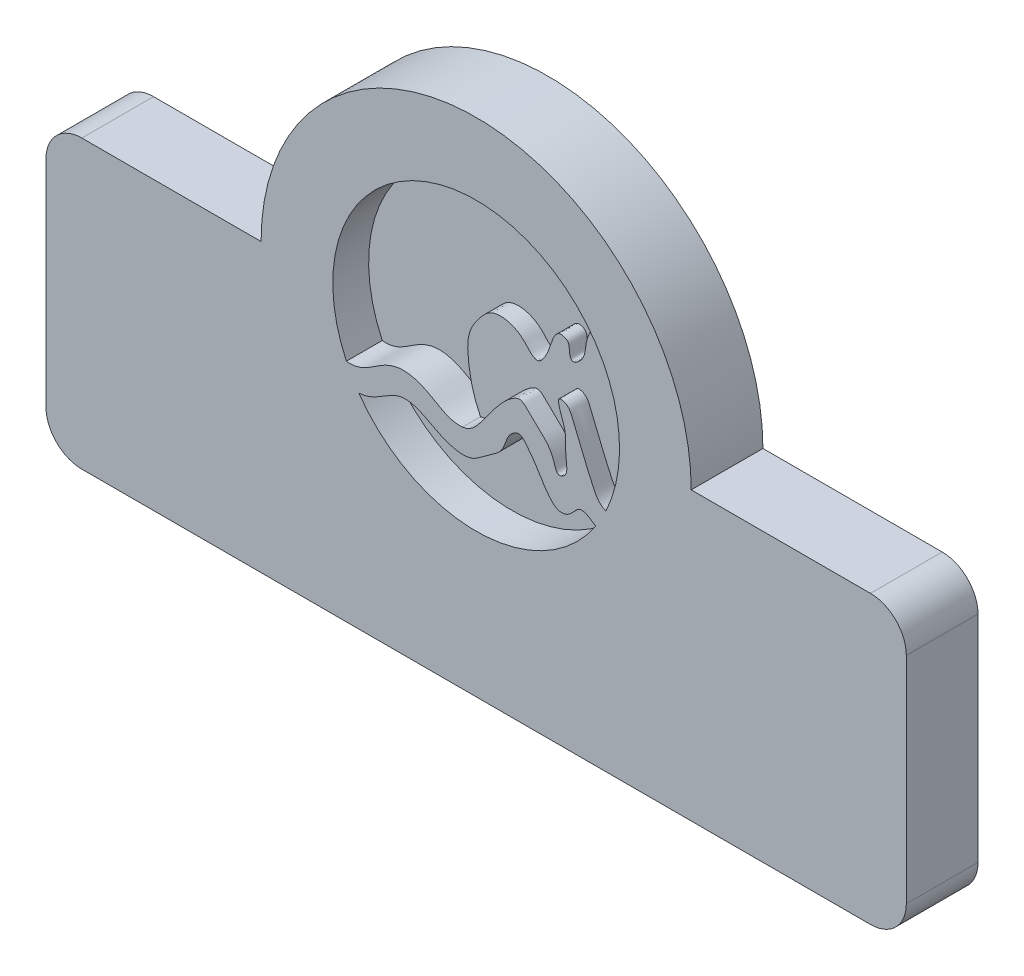
SolidWorks part; units mm, degrees
other "Camera1"
other "Camera2"
other "Camera3"
ref_plane "Front Plane" through (0, 0, 0) normal (0, 0, 1) x (1, 0, 0)
ref_plane "Top Plane" through (0, 0, 0) normal (0, 1, 0) x (1, 0, 0)
ref_plane "Right Plane" through (0, 0, 0) normal (1, 0, 0) x (0, 0, -1)
sketch "Sketch1" plane through (0, 0, 0) normal (0, 0, 1) x (1, 0, 0)
  line L0 (6.9108, 13.8216) -> (34.554, 13.8216) construction
  line L1 (6.9108, 13.8216) -> (34.554, 13.8216) construction
  line L2 (35.7853, 16.1395) -> (54.8353, 16.1395)
  line L3 (-21.3647, -9.2605) -> (54.8353, -9.2605)
  line L4 (-21.3647, -9.2605) -> (-21.3647, 16.1395)
  line L5 (-21.3647, 16.1395) -> (-2.3147, 16.1395)
  line L6 (54.8353, -9.2605) -> (54.8353, 16.1395)
  arc A0 (35.7853, 16.1395) -> (-2.3147, 16.1395) centre (16.7353, 16.1395) ccw
  point P10 (16.7353, -9.2605)
  dimension "D1" = 19.05
  dimension "D2" = 25.4
  dimension "D3" = 76.2
extrude "Boss-Extrude3" add sketch "Sketch1" along normal blind 6.35
sketch "Sketch2" plane through (0, 0, 0) normal (0, 0, 1) x (1, 0, 0)
  line L0 (6.9108, 13.8216) -> (34.554, 13.8216) construction
  line L1 (6.9108, 13.8216) -> (34.554, 13.8216) construction
  line L3 (-21.3647, -9.2605) -> (54.8353, -9.2605)
  line L4 (-21.3647, -9.2605) -> (-21.3647, 16.1395)
  line L5 (-21.3647, 16.1395) -> (4.0353, 16.1395)
  line L6 (54.8353, -9.2605) -> (54.8353, 16.1395)
  line L7 (29.4353, 16.1395) -> (54.8353, 16.1395)
  circle A0 centre (16.7353, 16.1395) radius 12.7
  spline S0 degree 3 poles (5.2422, 10.736) (6.7181, 10.5583) (7.9181, 12.0335) (10.4689, 12.7659) (12.4429, 12.0981) (14.04, 10.9311) (16.2264, 10.6186) (17.4992, 12.5179) (18.6877, 14.1015) (19.6579, 15.1072) (20.7366, 15.6711) (21.5924, 14.6574) (22.7186, 13.7475) (23.5698, 12.7033) (23.8626, 11.2746) (24.9534, 11.6978) (24.5407, 13.3498) (24.8083, 15.1398) (24.095, 16.3012) (23.9989, 17.3316) (24.934, 17.3133) (25.3682, 16.0395) (25.9915, 14.7265) (26.4068, 13.4846) (27.1285, 12.1461) (27.37, 11.104) (28.2285, 10.736) knots 0 0 0 0 0.103449 0.139242 0.205578 0.258602 0.299466 0.363653 0.418235 0.461509 0.476758 0.506043 0.548409 0.597042 0.622241 0.632003 0.675048 0.726967 0.779124 0.786559 0.795901 0.835777 0.878716 0.917237 0.938498 1 1 1 1
  spline S1 degree 3 poles (6.3413, 8.8418) (7.3529, 8.8928) (8.4397, 9.7204) (10.0783, 10.5483) (11.6016, 10.3368) (13.0104, 9.4793) (14.603, 8.7601) (16.3539, 8.6272) (17.6381, 9.777) (19.2522, 10.6455) (19.4083, 12.2512) (20.6019, 13.0206) (21.5067, 11.9378) (22.2898, 10.7945) (23.033, 9.4552) (23.9852, 8.5414) (25.1785, 8.7836) (25.8581, 10.2364) (27.0204, 9.3268) (27.3242, 9.1277) knots 0 0 0 0 0.111112 0.158804 0.207675 0.281443 0.349359 0.412439 0.469148 0.544608 0.609897 0.643349 0.67797 0.748785 0.815451 0.856727 0.888905 0.942631 1 1 1 1
  spline S2 degree 3 poles (15.5303, 10.8283) (14.8939, 12.0951) (14.4389, 13.9813) (14.3435, 16.7343) (15.2691, 18.2447) (16.5062, 19.5074) (18.14, 19.4662) (19.332, 18.7362) (19.9024, 17.9655) (20.6817, 17.4716) (21.4483, 18.509) (21.7334, 19.5035) (22.2913, 20.9391) (23.5141, 20.4969) (23.333, 19.7355) (23.6787, 18.9513) (24.8928, 19.8566) (24.7041, 21.7986) (25.937, 23.3158) (26.6866, 24.0301) knots 0 0 0 0 0.163827 0.228295 0.314759 0.363733 0.427294 0.487534 0.520272 0.543413 0.580046 0.637018 0.68948 0.715614 0.7546 0.768001 0.802503 0.870836 1 1 1 1
  dimension "D1" = 25.4
  dimension "D2" = 25.4
  dimension "D3" = 76.2
sketch "Sketch4" plane through (0, 0, 0) normal (0, 0, 1) x (1, 0, 0)
  line L0 (6.9108, 13.8216) -> (34.554, 13.8216) construction
  line L1 (6.9108, 13.8216) -> (34.554, 13.8216) construction
  line L3 (-21.3647, -9.2605) -> (54.8353, -9.2605)
  line L4 (-21.3647, -9.2605) -> (-21.3647, 16.1395)
  line L5 (-21.3647, 16.1395) -> (4.0353, 16.1395)
  line L6 (54.8353, -9.2605) -> (54.8353, 16.1395)
  line L7 (29.4353, 16.1395) -> (54.8353, 16.1395)
  circle A0 centre (16.7353, 16.1395) radius 12.7
  spline S0 degree 3 poles (5.2422, 10.736) (6.7181, 10.5583) (7.9181, 12.0335) (10.4689, 12.7659) (12.4429, 12.0981) (14.04, 10.9311) (16.2264, 10.6186) (17.4992, 12.5179) (18.6877, 14.1015) (19.6579, 15.1072) (20.7366, 15.6711) (21.5924, 14.6574) (22.7186, 13.7475) (23.5698, 12.7033) (23.8626, 11.2746) (24.9534, 11.6978) (24.5407, 13.3498) (24.8083, 15.1398) (24.095, 16.3012) (23.9989, 17.3316) (24.934, 17.3133) (25.3682, 16.0395) (25.9915, 14.7265) (26.4068, 13.4846) (27.1285, 12.1461) (27.37, 11.104) (28.2285, 10.736) knots 0 0 0 0 0.103449 0.139242 0.205578 0.258602 0.299466 0.363653 0.418235 0.461509 0.476758 0.506043 0.548409 0.597042 0.622241 0.632003 0.675048 0.726967 0.779124 0.786559 0.795901 0.835777 0.878716 0.917237 0.938498 1 1 1 1
  spline S1 degree 3 poles (6.3413, 8.8418) (7.3529, 8.8928) (8.4397, 9.7204) (10.0783, 10.5483) (11.6016, 10.3368) (13.0104, 9.4793) (14.603, 8.7601) (16.3539, 8.6272) (17.6381, 9.777) (19.2522, 10.6455) (19.4083, 12.2512) (20.6019, 13.0206) (21.5067, 11.9378) (22.2898, 10.7945) (23.033, 9.4552) (23.9852, 8.5414) (25.1785, 8.7836) (25.8581, 10.2364) (27.0204, 9.3268) (27.3242, 9.1277) knots 0 0 0 0 0.111112 0.158804 0.207675 0.281443 0.349359 0.412439 0.469148 0.544608 0.609897 0.643349 0.67797 0.748785 0.815451 0.856727 0.888905 0.942631 1 1 1 1
  spline S2 degree 3 poles (15.5303, 10.8283) (14.8939, 12.0951) (14.4389, 13.9813) (14.3435, 16.7343) (15.2691, 18.2447) (16.5062, 19.5074) (18.14, 19.4662) (19.332, 18.7362) (19.9024, 17.9655) (20.6817, 17.4716) (21.4483, 18.509) (21.7334, 19.5035) (22.2913, 20.9391) (23.5141, 20.4969) (23.333, 19.7355) (23.6787, 18.9513) (24.8928, 19.8566) (24.7041, 21.7986) (25.937, 23.3158) (26.6866, 24.0301) knots 0 0 0 0 0.163827 0.228295 0.314759 0.363733 0.427294 0.487534 0.520272 0.543413 0.580046 0.637018 0.68948 0.715614 0.7546 0.768001 0.802503 0.870836 1 1 1 1
  dimension "D1" = 25.4
  dimension "D2" = 25.4
  dimension "D3" = 76.2
extrude "Cut-Extrude2" cut sketch "Sketch2" against normal blind 3.175 from surface at 6.35 contours S0 S2 A0 | S1 A0
extrude "Cut-Extrude4" cut sketch "Sketch4" against normal blind 1.5875 from surface at 6.35 contours S2 S0 A0 starting at face at (10.272, 16.1659, 6.35)
fillet "Fillet1" radius 3.175 4 edges at (54.8353, 16.1395, 3.175) (54.8353, -9.2605, 3.175) (-21.3647, -9.2605, 3.175) (-21.3647, 16.1395, 3.175)
sketch "Sketch6" plane through (0, 0, 6.35) normal (0, 0, 1) x (1, 0, 0)
  line L0 (-21.3647, -6.0855) -> (54.8353, -6.0855)
